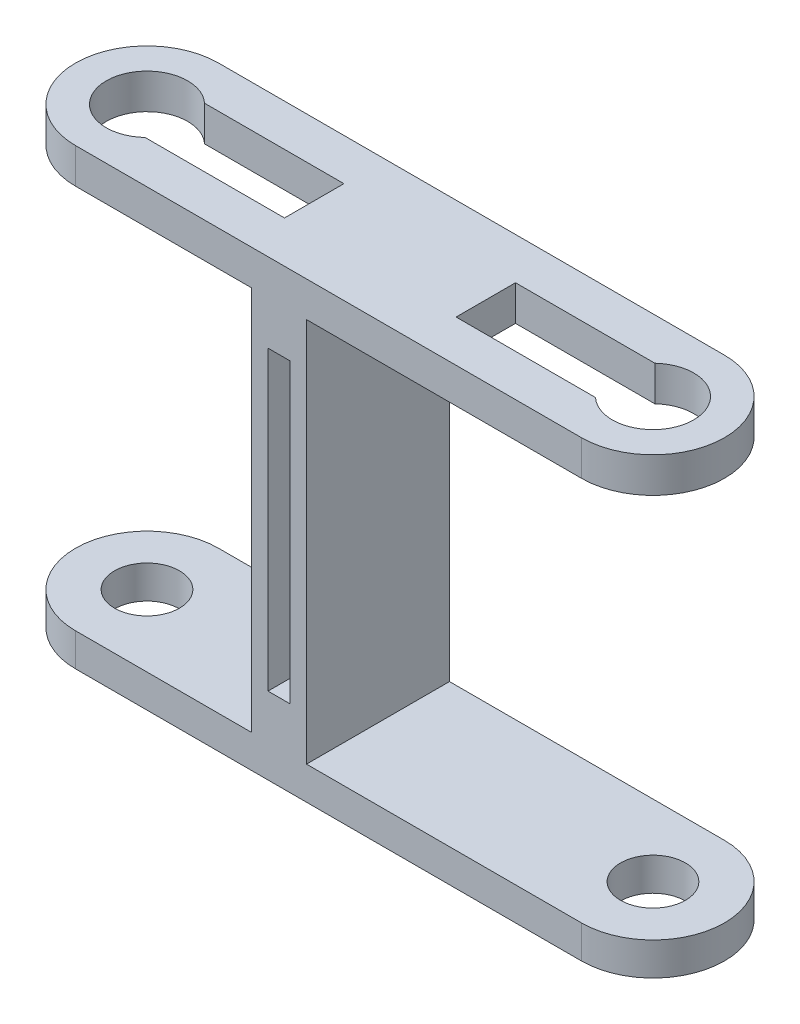
SolidWorks part; units mm, degrees
material "ABS"
ref_plane "Front Plane" through (0, 0, 0) normal (0, 0, 1) x (1, 0, 0)
ref_plane "Top Plane" through (0, 0, 0) normal (0, 1, 0) x (1, 0, 0)
ref_plane "Right Plane" through (0, 0, 0) normal (1, 0, 0) x (0, 0, -1)
sketch "Sketch1" plane through (0, 0, 0) normal (0, 1, 0) x (1, 0, 0)
  circle A0 centre (0, 0) radius 6.5
  circle A1 centre (46, 0) radius 6.5
extrude "Boss-Extrude1" add sketch "Sketch1" along normal mid plane 3.2 from offset 43.1
sketch "Sketch2" plane through (0, 0, 0) normal (0, 1, 0) x (1, 0, 0)
  line L1 (0, -6.5) -> (46, -6.5)
  line L2 (0, -6.5) -> (0, 6.5)
  line L3 (0, 6.5) -> (46, 6.5)
  line L4 (46, -6.5) -> (46, 6.5)
  circle A0 centre (0, 0) radius 6.5 construction
  circle A1 centre (46, 0) radius 6.5 construction
extrude "Boss-Extrude2" add sketch "Sketch2" along normal mid plane 3.2 from offset 43.1
sketch "Sketch3" plane through (0, 0, 0) normal (0, 1, 0) x (1, 0, 0)
  circle A0 centre (0, 0) radius 3.7
  circle A1 centre (46, 0) radius 3.7
extrude "Cut-Extrude1" cut sketch "Sketch3" against normal mid plane 3.2 from offset 43.1
sketch "Sketch4" plane through (0, 0, 0) normal (0, 1, 0) x (1, 0, 0)
  line L1 (0, -2.7) -> (15.2, -2.7)
  line L2 (0, -2.7) -> (0, 2.7)
  line L3 (0, 2.7) -> (15.2, 2.7)
  line L4 (15.2, -2.7) -> (15.2, 2.7)
  line L5 (30.8, -2.7) -> (46, -2.7)
  line L6 (30.8, -2.7) -> (30.8, 2.7)
  line L7 (30.8, 2.7) -> (46, 2.7)
  line L8 (46, -2.7) -> (46, 2.7)
extrude "Cut-Extrude2" cut sketch "Sketch4" against normal mid plane 3.2 from offset 43.1
sketch "Sketch5" plane through (0, 0, 0) normal (0, 1, 0) x (1, 0, 0)
  circle A0 centre (0, 0) radius 6.5
  circle A1 centre (46, 0) radius 6.5
extrude "Boss-Extrude3" add sketch "Sketch5" along normal mid plane 3 from offset 5
sketch "Sketch6" plane through (0, 0, 0) normal (0, 1, 0) x (1, 0, 0)
  line L1 (0, -6.5) -> (46, -6.5)
  line L2 (0, -6.5) -> (0, 6.5)
  line L3 (0, 6.5) -> (46, 6.5)
  line L4 (46, -6.5) -> (46, 6.5)
extrude "Boss-Extrude4" add sketch "Sketch6" along normal mid plane 3 from offset 5
sketch "Sketch7" plane through (0, 0, 0) normal (0, 1, 0) x (1, 0, 0)
  circle A0 centre (0, 0) radius 2.95
  circle A1 centre (46, 0) radius 2.95
extrude "Cut-Extrude3" cut sketch "Sketch7" against normal mid plane 3 from offset 5
sketch "Sketch8" plane through (0, 0, 0) normal (1, 0, 0) x (0, 0, -1)
  line L1 (-6.5, 3.5) -> (6.5, 3.5)
  line L2 (-6.5, 3.5) -> (-6.5, 44.7)
  line L3 (-6.5, 44.7) -> (6.5, 44.7)
  line L4 (6.5, 3.5) -> (6.5, 44.7)
extrude "Boss-Extrude5" add sketch "Sketch8" along normal mid plane 5 from offset 18.5
sketch "Sketch9" plane through (0, 0, 0) normal (0, 0, 1) x (1, 0, 0)
  line L1 (17.5, 10.5) -> (19.5, 10.5)
  line L2 (17.5, 10.5) -> (17.5, 37.5)
  line L3 (17.5, 37.5) -> (19.5, 37.5)
  line L4 (19.5, 10.5) -> (19.5, 37.5)
extrude "Cut-Extrude4" cut sketch "Sketch9" against normal mid plane 13.02 from offset 0.01
